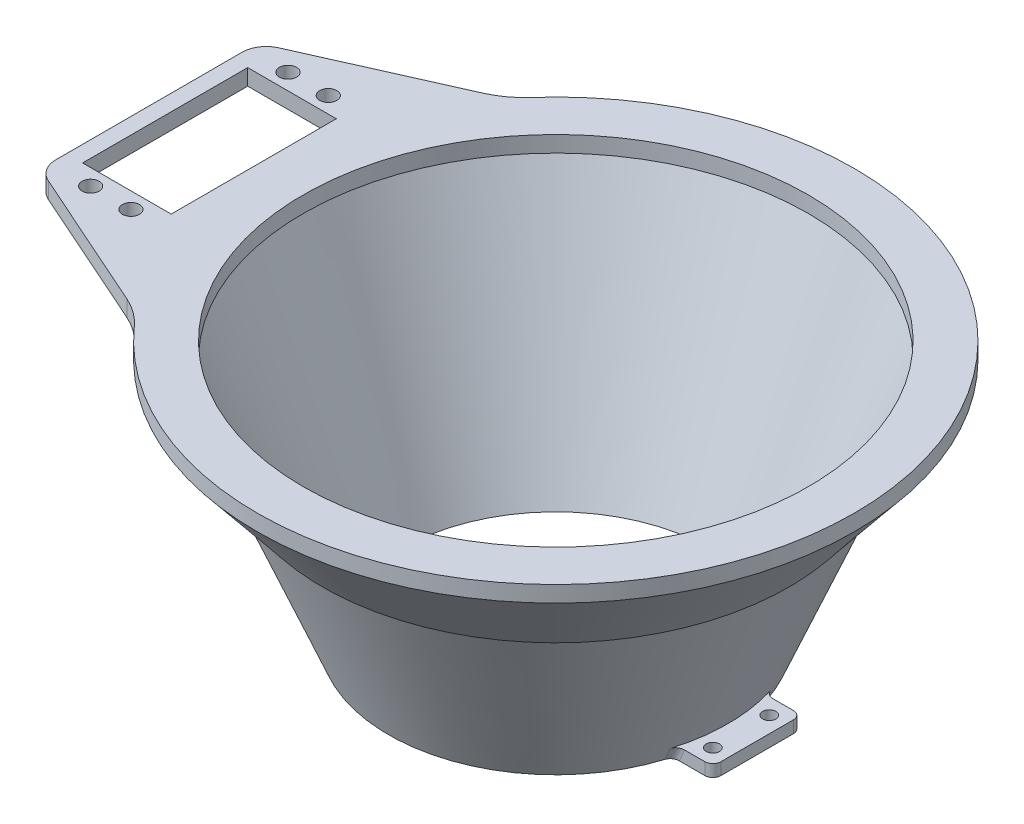
SolidWorks part; units mm, degrees
ref_plane "Front Plane" through (0, 0, 0) normal (0, 0, 1) x (1, 0, 0)
ref_plane "Top Plane" through (0, 0, 0) normal (0, 1, 0) x (1, 0, 0)
ref_plane "Right Plane" through (0, 0, 0) normal (1, 0, 0) x (0, 0, -1)
sketch "Sketch2" plane through (0, 0, 0) normal (0, 0, 1) x (1, 0, 0)
  line L0 (0, 0) -> (38.5, 0) construction
  line L1 (38.5, 0) -> (62.7416, 60)
  line L2 (38.5, 0) -> (41.5, 0) construction
  line L3 (41.5, 0) -> (66.1376, 60)
  line L4 (62.7416, 60) -> (66.1376, 60)
  line L5 (0, 0) -> (0, 42.1787) construction
  line L6 (38.5, 0) -> (41.5, 0)
  point P6 (65.7343, 60)
  point P7 (62.7416, 59.982)
  point P8 (65.8972, 59.0194)
  point P9 (66.1376, 60)
  dimension "D1" = 38.5
  dimension "D2" = 41.5
  dimension "D3" = 60
  dimension "D4" = 112
  dimension "D5" = 60
revolve "Revolve1" add sketch "Sketch2" angle 360 about L5
sketch "Sketch3" plane through (0, 0, 0) normal (0, -1, 0) x (1, 0, 0)
  line L0 (-50.0156, 11) -> (-40.0156, 11)
  line L1 (-50.0156, 11) -> (-50.0156, -11)
  line L2 (-50.0156, -11) -> (-40.0156, -11)
  line L3 (-50.0156, 0) -> (0, 0) construction
  line L4 (0, 0) -> (0, 25.3337) construction
  line L5 (50.0156, -11) -> (40.0156, -11)
  line L6 (50.0156, 11) -> (50.0156, -11)
  line L7 (50.0156, 11) -> (40.0156, 11)
  circle A0 centre (0, 0) radius 41.5 construction
  circle A1 centre (0, 0) radius 41.5 construction
  circle A2 centre (-46.0156, -7) radius 1.65
  arc A3 (-40.0156, -11) -> (-40.0156, 11) centre (0, 0) cw
  circle A4 centre (-46.0156, 7) radius 1.65
  circle A5 centre (46.0156, 7) radius 1.65
  arc A6 (40.0156, -11) -> (40.0156, 11) centre (0, 0) ccw
  circle A7 centre (46.0156, -7) radius 1.65
  dimension "D2" = 3.3
  dimension "D1" = 22
  dimension "D3" = 7
  dimension "D4" = 4
  dimension "D5" = 10
extrude "Boss-Extrude1" add sketch "Sketch3" against normal blind 3
fillet "Fillet1" radius 2 8 edges at (50.0156, 1.5, -11) (50.0156, 1.5, 11) (-50.0156, 1.5, 11) (-50.0156, 1.5, -11)
sketch "Sketch4" plane through (0, 60, 0) normal (0, 1, 0) x (1, 0, 0)
  line L0 (-86, 34.5374) -> (-86, -37.4895) construction
  line L1 (-108.9765, 0) -> (0, 0) construction
  line L2 (-101, 27) -> (-20, 63.0411)
  line L3 (-97, -20.5) -> (-75, -20.5)
  line L4 (-97, -20.5) -> (-97, 20.5)
  line L5 (-97, 20.5) -> (-75, 20.5)
  line L6 (-75, -20.5) -> (-75, 20.5)
  line L7 (-97, -20.5) -> (-75, 20.5) construction
  line L8 (-97, 20.5) -> (-75, -20.5) construction
  line L9 (-101, -27) -> (-71, -27) construction
  line L10 (-101, -27) -> (-101, 27)
  line L11 (-101, 27) -> (-71, 27) construction
  line L12 (-71, -27) -> (-71, 27) construction
  line L13 (-101, -27) -> (-71, 27) construction
  line L14 (-101, 27) -> (-71, -27) construction
  line L15 (-101, -27) -> (-20, -63.0411)
  line L17 (-20, -63.0411) -> (-20, -59.4685)
  circle A0 centre (-91, 24.5) radius 2.125
  circle A1 centre (-81, 24.5) radius 2.125
  circle A2 centre (-81, -24.5) radius 2.125
  circle A3 centre (-91, -24.5) radius 2.125
  circle A4 centre (0, 0) radius 66.1376 construction
  circle A8 centre (0, 0) radius 62.7416 construction
  circle A9 centre (0, 0) radius 62.7416
  arc A10 (-33.4397, -57.0611) -> (-33.4397, 57.0611) centre (0, 0) ccw
  point P13 (-86, 0)
  point P16 (-86, 0)
  point P26 (0, 0)
  point P32 (-18.973, 59.8041)
  point P33 (-18.973, 59.8041)
  dimension "D1" = 4.25
  dimension "D2" = 5
  dimension "D3" = 24.5
  dimension "D4" = 86
  dimension "D5" = 22
  dimension "D6" = 41
  dimension "D7" = 54
  dimension "D8" = 30
  dimension "D9" = 20
extrude "Boss-Extrude2" add sketch "Sketch4" along normal blind 4 separate body
sketch "Sketch6" plane through (0, 0, 0) normal (0, 0, 1) x (1, 0, 0)
  line L0 (-66.1376, 60) -> (-74.1376, 60)
  line L1 (-101, 60) -> (-20, 60) construction
  line L2 (-74.1376, 60) -> (-57.9251, 40)
  line L3 (-66.1376, 60) -> (-42.7319, 3) construction
  line L4 (-57.9251, 40) -> (-66.1376, 60)
  line L5 (0, 0) -> (0, 90.5033) construction
  dimension "D1" = 8
  dimension "D2" = 20
revolve "Revolve5" add sketch "Sketch6" angle 360 about L5
sketch "Sketch7" plane through (0, 60, 0) normal (0, 1, 0) x (1, 0, 0)
  line L2 (-58.0551, 46.1084) -> (-20, 63.0411)
  line L3 (-20, -63.0411) -> (-58.0551, -46.1084)
  line L4 (-58.0551, 46.1084) -> (-20, 63.0411)
  line L5 (-20, -63.0411) -> (-58.0551, -46.1084)
  arc A2 (-58.0551, -46.1084) -> (-58.0551, 46.1084) centre (0, 0) ccw
  arc A3 (-20, -63.0411) -> (-20, 63.0411) centre (0, 0) ccw
  arc A4 (-58.0551, -46.1084) -> (-58.0551, 46.1084) centre (0, 0) ccw
  arc A5 (-20, -63.0411) -> (-20, 63.0411) centre (0, 0) ccw
  dimension "D1" = 0
extrude "Boss-Extrude3" add sketch "Sketch7" along normal blind 4
fillet "Fillet4" radius 20 2 edges at (-58.0551, 62, 46.1084) (-58.0551, 62, -46.1084)
fillet "Fillet5" radius 6 2 edges at (-101, 62, -27) (-101, 62, 27)
